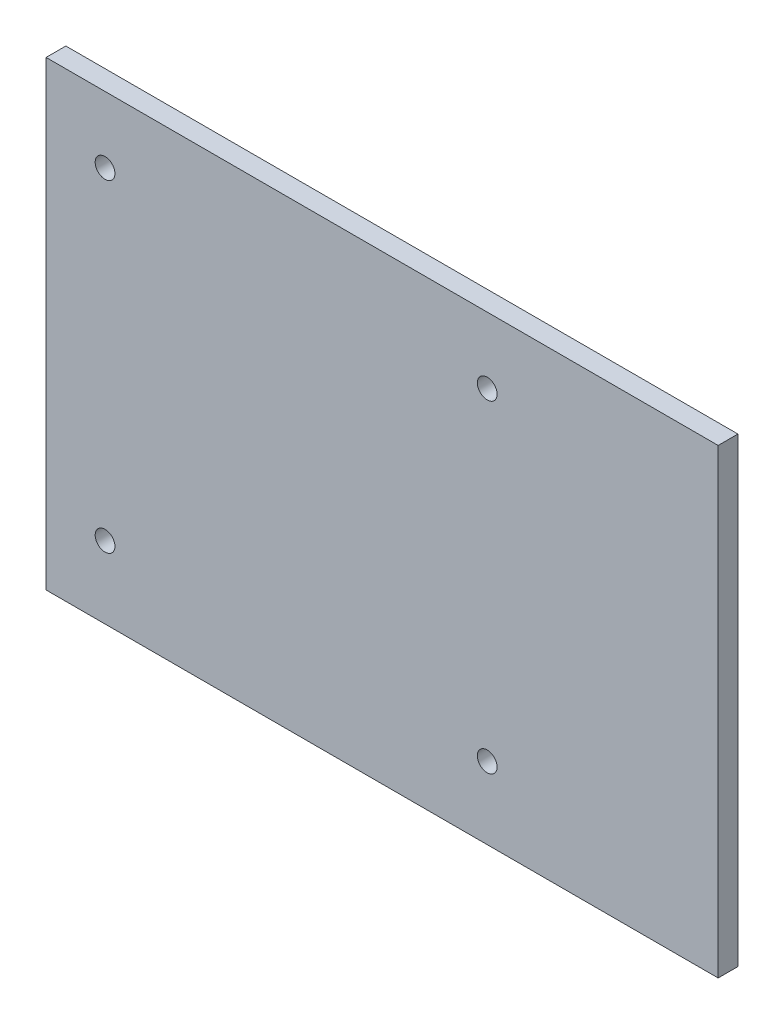
SolidWorks part; units mm, degrees
ref_plane "Front Plane" through (0, 0, 0) normal (0, 0, 1) x (1, 0, 0)
ref_plane "Top Plane" through (0, 0, 0) normal (0, 1, 0) x (1, 0, 0)
ref_plane "Right Plane" through (0, 0, 0) normal (1, 0, 0) x (0, 0, -1)
sketch "Sketch1" plane through (0, 0, 0) normal (0, 0, 1) x (1, 0, 0)
  line L0 (-26.6591, -15.2669) -> (4.7676, -15.2669) construction
  line L1 (-26.6591, 19.2831) -> (75.3409, 19.2831)
  line L2 (-26.6591, 19.2831) -> (-26.6591, -50.7169)
  line L3 (-26.6591, -50.7169) -> (75.3409, -50.7169)
  line L4 (75.3409, 19.2831) -> (75.3409, -50.7169)
  line L5 (11.2909, -50.7169) -> (11.2909, -16.8422) construction
  circle A0 centre (-17.7091, -39.7669) radius 1.5
  circle A1 centre (-17.7091, 9.2331) radius 1.5
  circle A2 centre (40.2909, -39.7669) radius 1.5
  circle A3 centre (40.2909, 9.2331) radius 1.5
  dimension "D3" = 3
  dimension "D4" = 10.95
  dimension "D5" = 8.95
  dimension "D1" = 102
  dimension "D2" = 70
  dimension "D6" = 24.5
  dimension "D7" = 29
extrude "Boss-Extrude1" add sketch "Sketch1" along normal blind 3
